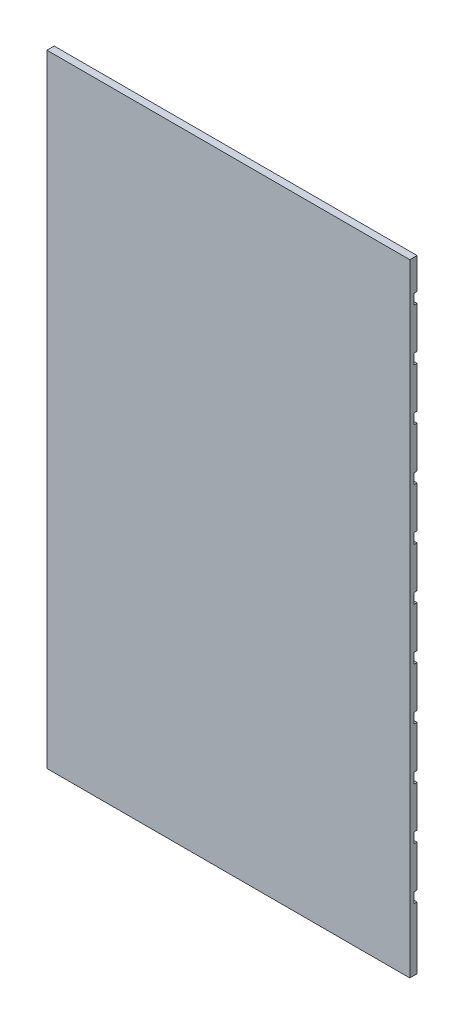
SolidWorks part; units mm, degrees
ref_plane "Front Plane" through (0, 0, 0) normal (0, 0, 1) x (1, 0, 0)
ref_plane "Top Plane" through (0, 0, 0) normal (0, 1, 0) x (1, 0, 0)
ref_plane "Right Plane" through (0, 0, 0) normal (1, 0, 0) x (0, 0, -1)
sketch "Sketch2" plane through (0, 0, 0) normal (1, 0, 0) x (0, 0, -1)
  line L1 (0, 0) -> (17.78, 0)
  line L2 (0, 0) -> (0, -1524)
  line L3 (0, -1524) -> (17.78, -1524)
  line L4 (17.78, 0) -> (17.78, -1524)
  dimension "D1" = 17.78
  dimension "D2" = 1524
extrude "Boss-Extrude1" add sketch "Sketch2" along normal blind 889
sketch "Sketch3" plane through (0, 0, -17.78) normal (0, 0, -1) x (-1, 0, 0)
  line L0 (-889, -1524) -> (-889, 0) construction
  line L1 (-889, -76.2) -> (0, -76.2)
  line L2 (-889, -76.2) -> (-889, -101.6)
  line L3 (-889, -101.6) -> (0, -101.6)
  line L4 (0, -76.2) -> (0, -101.6)
  line L5 (0, -1524) -> (0, 0) construction
  line L6 (-889, 0) -> (0, 0) construction
  line L7 (-889, -228.6) -> (0, -228.6)
  line L8 (-889, -203.2) -> (0, -203.2)
  line L9 (-889, -203.2) -> (-889, -228.6)
  line L10 (0, -203.2) -> (0, -228.6)
  line L11 (-889, -355.6) -> (0, -355.6)
  line L12 (-889, -330.2) -> (0, -330.2)
  line L13 (-889, -330.2) -> (-889, -355.6)
  line L14 (0, -330.2) -> (0, -355.6)
  line L15 (-889, -482.6) -> (0, -482.6)
  line L16 (-889, -457.2) -> (0, -457.2)
  line L17 (-889, -457.2) -> (-889, -482.6)
  line L18 (0, -457.2) -> (0, -482.6)
  line L19 (-889, -609.6) -> (0, -609.6)
  line L20 (-889, -584.2) -> (0, -584.2)
  line L21 (-889, -584.2) -> (-889, -609.6)
  line L22 (0, -584.2) -> (0, -609.6)
  line L23 (-889, -736.6) -> (0, -736.6)
  line L24 (-889, -711.2) -> (0, -711.2)
  line L25 (-889, -711.2) -> (-889, -736.6)
  line L26 (0, -711.2) -> (0, -736.6)
  line L27 (-889, -863.6) -> (0, -863.6)
  line L28 (-889, -838.2) -> (0, -838.2)
  line L29 (-889, -838.2) -> (-889, -863.6)
  line L30 (0, -838.2) -> (0, -863.6)
  line L31 (-889, -990.6) -> (0, -990.6)
  line L32 (-889, -965.2) -> (0, -965.2)
  line L33 (-889, -965.2) -> (-889, -990.6)
  line L34 (0, -965.2) -> (0, -990.6)
  line L35 (-889, -1117.6) -> (0, -1117.6)
  line L36 (-889, -1092.2) -> (0, -1092.2)
  line L37 (-889, -1092.2) -> (-889, -1117.6)
  line L38 (0, -1092.2) -> (0, -1117.6)
  line L39 (-889, -1244.6) -> (0, -1244.6)
  line L40 (-889, -1219.2) -> (0, -1219.2)
  line L41 (-889, -1219.2) -> (-889, -1244.6)
  line L42 (0, -1219.2) -> (0, -1244.6)
  line L43 (-889, -1371.6) -> (0, -1371.6)
  line L44 (-889, -1346.2) -> (0, -1346.2)
  line L45 (-889, -1346.2) -> (-889, -1371.6)
  line L46 (0, -1346.2) -> (0, -1371.6)
  dimension "D1" = 25.4
  dimension "D2" = 76.2
  dimension "D3" = 11
extrude "Cut-Extrude1" cut sketch "Sketch3" against normal blind 7.62
